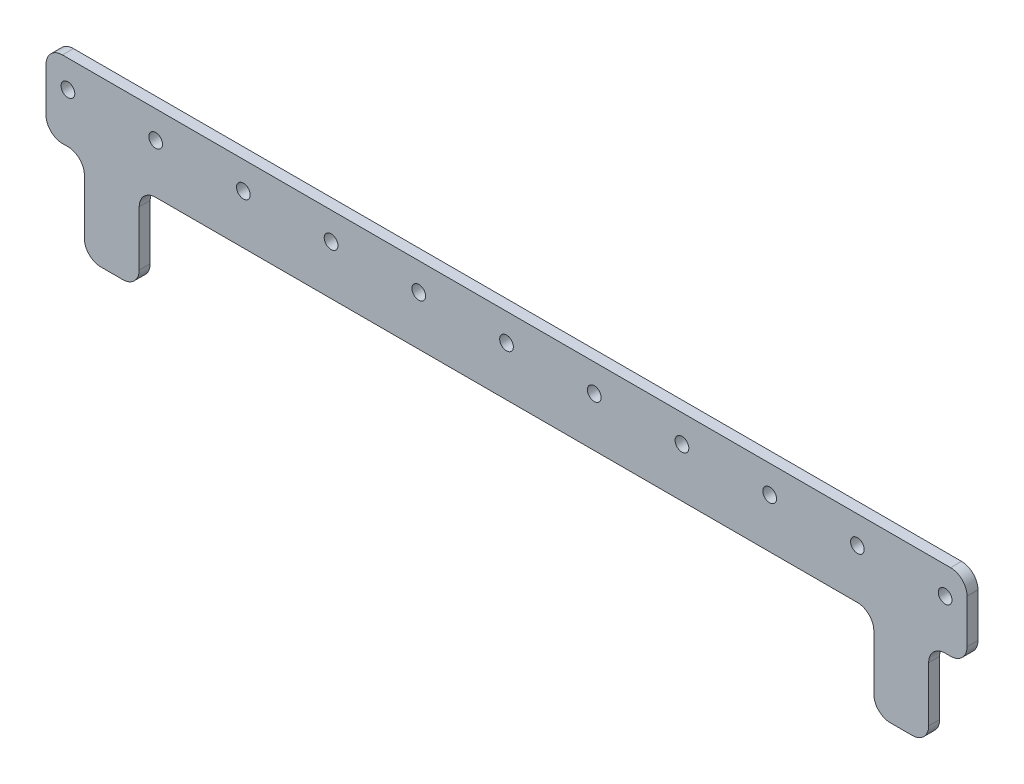
SolidWorks part; units mm, degrees
ref_plane "Top" through (0, 0, 0) normal (0, 0, 1) x (1, 0, 0)
ref_plane "Front" through (0, 0, 0) normal (0, 1, 0) x (1, 0, 0)
ref_plane "Right" through (0, 0, 0) normal (1, 0, 0) x (0, 0, -1)
sketch "Base Sketch" plane through (0, 0, 0) normal (0, 0, 1) x (1, 0, 0)
  line L0 (-84, 7) -> (84, -7) construction
  line L1 (-84, 7) -> (84, 7)
  line L2 (-84, 7) -> (-84, -7)
  line L3 (-84, -7) -> (84, -7)
  line L4 (84, 7) -> (84, -7)
  point P4 (0, 0)
  dimension "Length" = 168
  dimension "D2" = 14
extrude "Base Extrude" add sketch "Base Sketch" against normal blind 2
sketch "Pin Hole Sketch" plane through (0, 0, 0) normal (0, 0, 1) x (1, 0, 0)
  line L0 (84, -7) -> (84, 7) construction
  line L1 (84, 7) -> (-84, 7) construction
  circle A0 centre (80, 2) radius 1.25
  dimension "Diameter" = 2.5
  dimension "D1" = 4
  dimension "D2" = 5
extrude "First Pin Hole Cut" cut sketch "Pin Hole Sketch" against normal through all
pattern_linear "Pin Hole Pattern" count 11 spacing 16 along (-1, 0, 0) of "First Pin Hole Cut"
sketch "Extension Sketch" plane through (0, 0, 0) normal (0, 0, 1) x (1, 0, 0)
  line L0 (64, 2) -> (80, 2) construction
  line L1 (72, 2) -> (72, -23) construction
  line L2 (67, -23) -> (77, -23)
  line L3 (77, -23) -> (77, 2)
  line L4 (77, 2) -> (67, 2)
  line L5 (67, 2) -> (67, -23)
  line L6 (84, 7) -> (-84, 7) construction
  circle A0 centre (80, 2) radius 1.25 construction
  circle A1 centre (64, 2) radius 1.25 construction
  dimension "D1" = 10
  dimension "D2" = 30
extrude "Tab Extrude" add sketch "Extension Sketch" against normal through all separate body
mirror "Tab Mirror" about plane through (0, 0, 0) normal (1, 0, 0) of "Tab Extrude"
combine bodies "Combine Bodies" operation type add bodies to combine 106 105
fillet "Corner Fillets" radius 3 12 edges at (84, 7, -1) (84, -7, -1) (-84, -7, -1) (-84, 7, -1) (67, -7, -1) (-77, -7, -1) (-67, -7, -1) (77, -7, -1) (-77, -23, -1) (-67, -23, -1) (67, -23, -1) (77, -23, -1)
